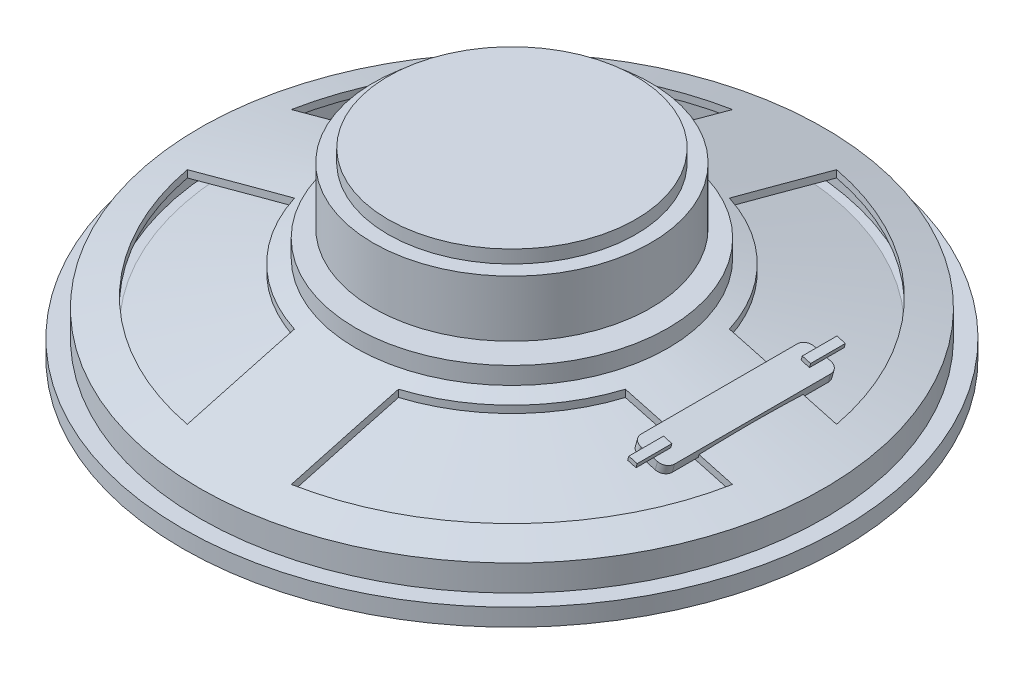
SolidWorks part; units mm, degrees
ref_plane "Plan1" through (0, 0, 0) normal (0, 0, 1) x (1, 0, 0)
ref_plane "Plan2" through (0, 0, 0) normal (0, 1, 0) x (1, 0, 0)
ref_plane "Plan3" through (0, 0, 0) normal (1, 0, 0) x (0, 0, -1)
sketch "Esquisse1" plane through (0, 0, 0) normal (0, 0, 1) x (1, 0, 0)
  line L0 (0, 0) -> (-16, 0)
  line L1 (-16, 0) -> (-16, -8)
  line L2 (-16, -8) -> (-10, -8)
  line L3 (-10, -8) -> (-10, -9)
  line L4 (-10, -9) -> (-18, -9)
  line L5 (-18, -9) -> (-18, -11)
  line L6 (-18, -11) -> (-36, -16)
  line L7 (-36, -16) -> (-36, -19)
  line L8 (-36, -19) -> (-38, -19)
  line L9 (-38, -19) -> (-38, -21)
  line L10 (-38, -21) -> (-32, -21)
  line L11 (-32, -21) -> (-32, -19)
  line L12 (-32, -19) -> (-30, -19)
  line L13 (-30, -19) -> (-30, -21)
  line L14 (-30, -21) -> (-10, -16)
  line L15 (0, -19.8661) -> (0, 0)
  line L16 (0, 70) -> (0, -100) construction
  arc A0 (-10, -16) -> (0, -19.8661) centre (0, -5) ccw
  dimension "D9" = 5
  dimension "D1" = 38
  dimension "D2" = 36
  dimension "D3" = 32
  dimension "D4" = 30
  dimension "D5" = 18
  dimension "D6" = 16
  dimension "D7" = 10
  dimension "D8" = 10
  dimension "D10" = 8
  dimension "D11" = 1
  dimension "D12" = 2
  dimension "D13" = 3
  dimension "D14" = 2
  dimension "D15" = 2
  dimension "D16" = 2
  dimension "D17" = 16
  dimension "D19" = 21
revolve "Base-Révolution" add sketch "Esquisse1" angle 360 about L16
sketch "Esquisse2" plane through (0, 0, 0) normal (0, 0, 1) x (1, 0, 0)
  line L0 (-33.011, -16) -> (-15.011, -11)
  line L1 (-10, -16) -> (-30, -21) construction
  line L2 (-15.011, -11) -> (-5.3, -11)
  line L3 (-18, -11) -> (-36, -16) construction
  line L4 (-33.011, -16) -> (-33.011, -18)
  line L5 (36, -16) -> (-36, -16) construction
  line L6 (18, -11) -> (-18, -11) construction
  line L8 (-33.011, -18) -> (-32, -18)
  line L9 (-5.3, -11.325) -> (-5.3, -11)
  line L10 (-16, 0) -> (-16, -8) construction
  line L11 (-16, -1.5) -> (-14.2875, -1.5)
  line L12 (-16, -1.5) -> (-16, 0)
  line L13 (-16, 0) -> (-14.2875, 0)
  line L14 (-14.2875, -1.5) -> (-14.2875, 0)
  line L15 (0, 0) -> (0, -28.7) construction
  line L16 (0, 70) -> (0, -100) construction
  line L17 (-32, -18) -> (-5.3, -11.325)
  dimension "D1" = 0.8
  dimension "D2" = 3.3955
  dimension "D3" = 2
revolve "Enlèvement de matière-Révolution1" cut sketch "Esquisse2" angle 360 about L15
sketch "Esquisse3" plane through (0, 0, 0) normal (0, 1, 0) x (1, 0, 0)
  line L0 (6, 19.0788) -> (6, 31.4325)
  line L1 (-6, 19.0788) -> (-6, 31.4325)
  line L2 (-31.4325, 6) -> (-19.0788, 6)
  line L3 (-19.0788, -6) -> (-31.4325, -6)
  line L4 (-6, -19.0788) -> (-6, -31.4325)
  line L5 (6, -19.0788) -> (6, -31.4325)
  line L6 (19.0788, -6) -> (31.4325, -6)
  line L7 (19.0788, 6) -> (31.4325, 6)
  arc A0 (-6, 31.4325) -> (-31.4325, 6) centre (0, 0) ccw
  arc A1 (-31.4325, -6) -> (-6, -31.4325) centre (0, 0) ccw
  arc A2 (6, -31.4325) -> (31.4325, -6) centre (0, 0) ccw
  arc A3 (31.4325, 6) -> (6, 31.4325) centre (0, 0) ccw
  arc A4 (-19.0788, 6) -> (-6, 19.0788) centre (0, 0) cw
  arc A5 (6, 19.0788) -> (19.0788, 6) centre (0, 0) cw
  arc A6 (19.0788, -6) -> (6, -19.0788) centre (0, 0) cw
  arc A7 (-19.0788, -6) -> (-6, -19.0788) centre (0, 0) ccw
  dimension "D7" = 20
  dimension "D8" = 32
  dimension "D1" = 12
  dimension "D2" = 12
  dimension "D3" = 12
  dimension "D4" = 12
  dimension "D5" = 6
  dimension "D6" = 6
extrude "Enlèv. mat.-Extru.2" cut sketch "Esquisse3" against normal up to surface (12.3858 mm away)
ref_plane "Plan4" through (27, -13.5, 0) normal (0.2676, 0.9635, 0) x (0, 0, -1)
sketch "Esquisse4" plane through (27, -13.5, 0) normal (0.2676, 0.9635, 0) x (0, 0, -1)
  line L0 (6, -4.6425) -> (6, 8.1527) construction
  line L1 (-9, 3.3575) -> (9, 3.3575)
  line L2 (-10, 2.3575) -> (-10, 0.3575)
  line L3 (-9, -0.6425) -> (9, -0.6425)
  line L4 (10, 2.3575) -> (10, 0.3575)
  line L6 (-6, 8.1527) -> (-6, -4.6425) construction
  arc A0 (-9, -0.6425) -> (-10, 0.3575) centre (-9, 0.3575) cw
  arc A1 (-10, 2.3575) -> (-9, 3.3575) centre (-9, 2.3575) cw
  arc A2 (10, 2.3575) -> (9, 3.3575) centre (9, 2.3575) ccw
  arc A3 (10, 0.3575) -> (9, -0.6425) centre (9, 0.3575) cw
  point P15 (10, 3.3575)
  point P18 (10, -0.6425)
  dimension "D4" = 1
  dimension "D1" = 4
  dimension "D2" = 4
  dimension "D3" = 4
  dimension "D5" = 8
extrude "Boss.-Extru.2" add sketch "Esquisse4" along normal mid plane 1
sketch "Esquisse5" plane through (-1.4135, -5.0884, 0) normal (0.2676, 0.9635, 0) x (-0.9635, 0.2676, 0)
  line L0 (-30.2707, 9) -> (-30.2707, -9) construction
  line L1 (-28.7707, 12) -> (-27.7707, 12)
  line L2 (-28.7707, 12) -> (-28.7707, 8)
  line L3 (-28.7707, 8) -> (-27.7707, 8)
  line L4 (-27.7707, 12) -> (-27.7707, 8)
  line L5 (-28.7707, -8) -> (-27.7707, -8)
  line L6 (-28.7707, -8) -> (-28.7707, -12)
  line L7 (-28.7707, -12) -> (-27.7707, -12)
  line L8 (-27.7707, -8) -> (-27.7707, -12)
  line L9 (-27.2707, 10) -> (-29.2707, 10) construction
  line L10 (-29.2707, -10) -> (-27.2707, -10) construction
  dimension "D1" = 4
  dimension "D2" = 4
  dimension "D3" = 1
  dimension "D4" = 1
  dimension "D5" = 1.5
  dimension "D6" = 1.5
  dimension "D7" = 2
  dimension "D8" = 2
extrude "Boss.-Extru.3" add sketch "Esquisse5" along normal blind 0.5
